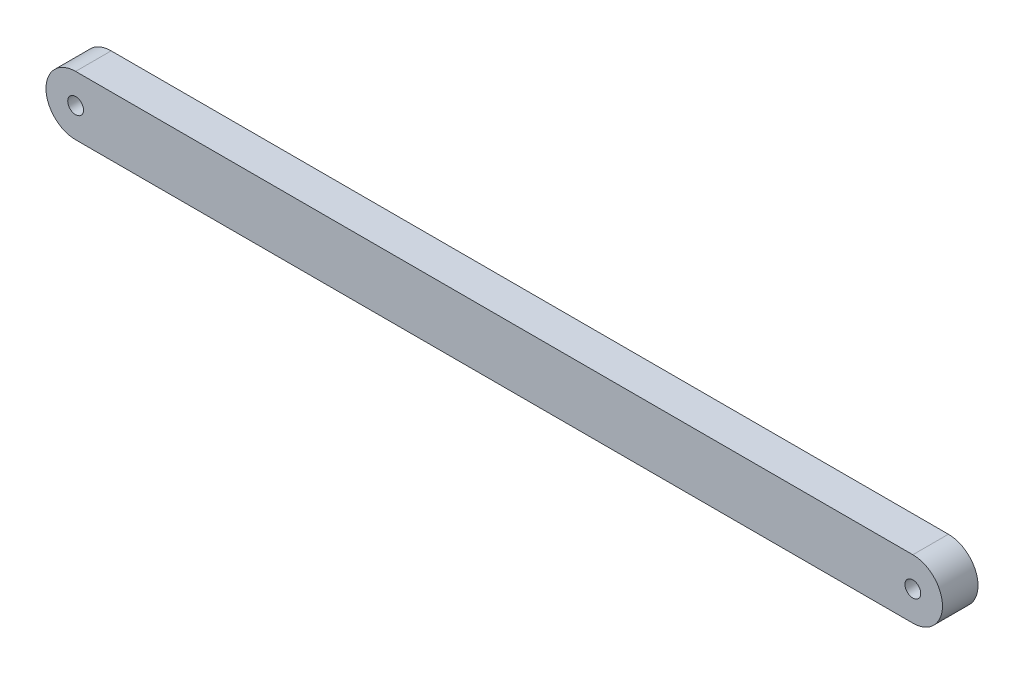
SolidWorks part; units mm, degrees
ref_plane "前视基准面" through (0, 0, 0) normal (0, 0, 1) x (1, 0, 0)
ref_plane "上视基准面" through (0, 0, 0) normal (0, 1, 0) x (1, 0, 0)
ref_plane "右视基准面" through (0, 0, 0) normal (1, 0, 0) x (0, 0, -1)
other "Configuration Table"
sketch "草图1" plane through (0, 0, 0) normal (0, 0, 1) x (1, 0, 0)
  line L0 (0, 15) -> (423.93, 15)
  line L1 (0, -15) -> (423.93, -15)
  arc A2 (0, 15) -> (0, -15) centre (0, 0) ccw
  arc A3 (423.93, -15) -> (423.93, 15) centre (423.93, 0) ccw
  circle A4 centre (0, 0) radius 4
  circle A5 centre (423.93, 0) radius 4
extrude "凸台-拉伸2" add sketch "草图1" along normal blind 18
